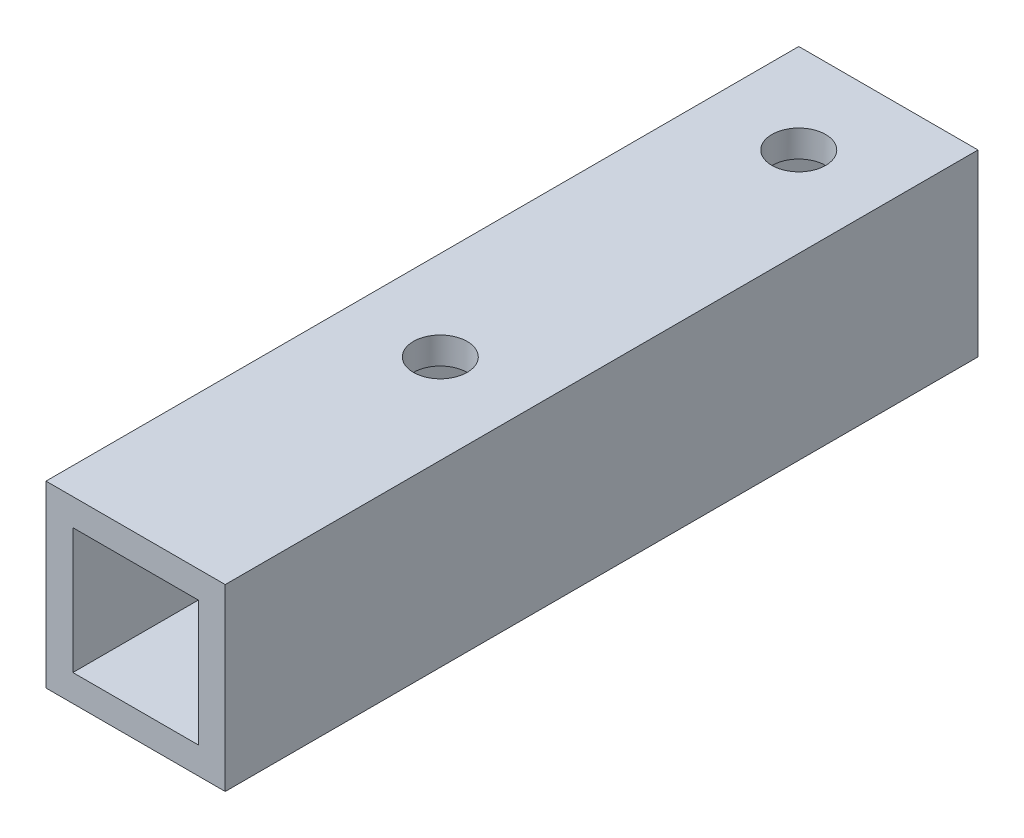
SolidWorks part; units mm, degrees
material "1060 合金"
ref_plane "正面" through (0, 0, 0) normal (0, 0, 1) x (1, 0, 0)
ref_plane "平面" through (0, 0, 0) normal (0, 1, 0) x (1, 0, 0)
ref_plane "右側面" through (0, 0, 0) normal (1, 0, 0) x (0, 0, -1)
sketch "ｽｹｯﾁ1" plane through (0, 0, 0) normal (0, 0, 1) x (1, 0, 0)
  line L1 (-5, -5) -> (5, -5)
  line L2 (-5, -5) -> (-5, 5)
  line L3 (-5, 5) -> (5, 5)
  line L4 (5, -5) -> (5, 5)
  line L5 (-5, -5) -> (5, 5) construction
  line L6 (-5, 5) -> (5, -5) construction
  point P0 (0, 0)
  dimension "D1" = 10
extrude "押し出し-薄板1" add sketch "ｽｹｯﾁ1" along normal blind 42 thin thin type one direction reverse wall 1.5
sketch "ｽｹｯﾁ2" plane through (0, 5, 0) normal (0, 1, 0) x (1, 0, 0)
  line L0 (0, 0) -> (0, -42) construction
  line L1 (5, -42) -> (-5, -42) construction
  line L2 (5, 0) -> (-5, 0) construction
  circle A0 centre (0, -5) radius 1.5
  circle A1 centre (0, -25) radius 1.5
  dimension "D1" = 5
  dimension "D2" = 20
  dimension "D3" = 3
extrude "ｶｯﾄ - 押し出し1" cut sketch "ｽｹｯﾁ2" against normal through all
